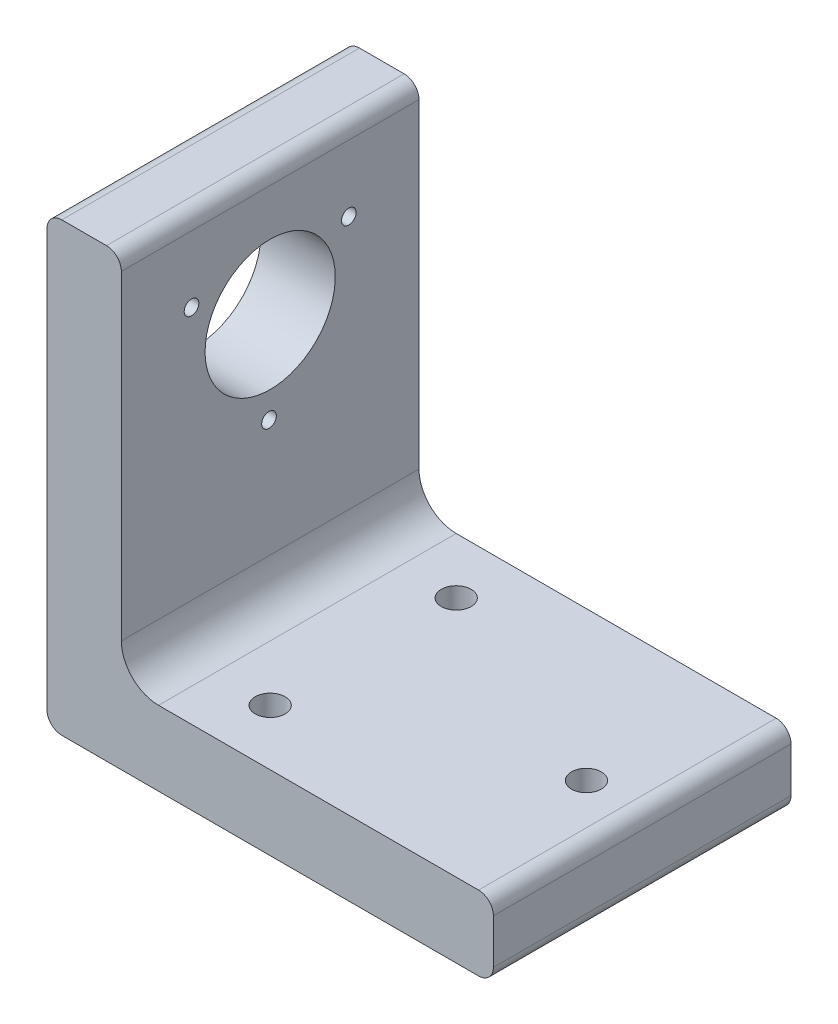
SolidWorks part; units mm, degrees
material "6061 Alloy"
ref_plane "Front" through (0, 0, 0) normal (0, 0, 1) x (1, 0, 0)
ref_plane "Top" through (0, 0, 0) normal (0, 1, 0) x (1, 0, 0)
ref_plane "Right" through (0, 0, 0) normal (1, 0, 0) x (0, 0, -1)
sketch "Sketch1" plane through (0, 0, 0) normal (0, 0, 1) x (1, 0, 0)
  line L0 (0, 0) -> (0, 76.2)
  line L1 (0, -50) -> (0, 50) construction
  line L2 (0, 76.2) -> (12.7, 76.2)
  line L3 (12.7, 76.2) -> (12.7, 12.7)
  line L4 (12.7, 12.7) -> (76.2, 12.7)
  line L5 (76.2, 12.7) -> (76.2, 0)
  line L6 (50, 0) -> (-50, 0) construction
  line L7 (76.2, 0) -> (0, 0)
  dimension "D1" = 76.2
  dimension "D2" = 12.7
extrude "Boss-Extrude1" add sketch "Sketch1" along normal blind 50.8
fillet "Fillet1" radius 2.54 5 edges at (12.7, 76.2, 25.4) (0, 76.2, 25.4) (0, 0, 25.4) (76.2, 0, 25.4) (76.2, 12.7, 25.4)
fillet "Fillet2" radius 6.35 1 edges at (12.7, 12.7, 25.4)
sketch "Sketch2" plane through (12.7, 0, 0) normal (1, 0, 0) x (0, 0, -1)
  line L0 (-50.8, 54.61) -> (0, 54.61) construction
  line L1 (-50.8, 19.05) -> (-50.8, 73.66) construction
  line L2 (0, 19.05) -> (0, 73.66) construction
  line L3 (-50.8, 76.2) -> (0, 76.2) construction
  circle A0 centre (-25.4, 54.61) radius 11.1125
  dimension "D1" = 22.225
  dimension "D2" = 21.59
extrude "Cut-Extrude1" cut sketch "Sketch2" against normal through all
hole_wizard "M3x0.5 Tapped Hole1" positions "Sketch3" profile "Sketch4" tap size "M3x0.5" standard "ANSI Metric" end condition up to next
sketch "Sketch3" plane through (12.7, 0, 0) normal (1, 0, 0) x (0, 0, -1)
  line L0 (-38.8234, 62.36) -> (-25.4, 54.61) construction
  line L1 (-25.4, 54.61) -> (-25.4, 39.11) construction
  line L3 (-25.4, 54.61) -> (-11.9766, 62.36) construction
  circle A0 centre (-25.4, 54.61) radius 15.5 construction
  circle A1 centre (-25.4, 54.61) radius 11.1125 construction
  point P0 (-38.8234, 62.36)
  point P2 (-11.9766, 62.36)
  point P4 (-25.6015, 39.1113)
  dimension "D1" = 31
  dimension "D2" = 120
  dimension "D3" = 120
sketch "Sketch4" plane through (12.7, 62.36, 38.8234) normal (0, 1, 0) x (0, 0, -1)
  line L0 (0, 0) -> (0, 12.7)
  line L1 (0, 12.7) -> (1.25, 12.7)
  line L2 (1.25, 12.7) -> (1.25, 0)
  line L5 (1.25, 0) -> (0, 0)
  line L11 (0, -6.35) -> (0, 107.95) construction
  dimension "Thru Tap Drill Dia." = 2.5
  dimension "Thru Tap Drill Depth" = 12.7
cosmetic thread "Hole Thread1" parameters "D2"=3
cosmetic thread "Hole Thread2" parameters "D2"=3
cosmetic thread "Hole Thread3" parameters "D2"=3
hole_wizard "1/4-20 Tapped Hole1" positions "Sketch5" profile "Sketch6" tap size "1/4-20" standard "ANSI Inch" end condition up to next
sketch "Sketch5" plane through (0, 12.7, 0) normal (0, 1, 0) x (1, 0, 0)
  line L0 (66.675, -25.4) -> (76.2, -25.4) construction
  line L1 (76.2, 0) -> (76.2, -50.8) construction
  line L3 (28.575, 0) -> (28.575, -9.525) construction
  line L4 (73.66, 0) -> (19.05, 0) construction
  line L7 (28.575, -41.275) -> (28.575, -50.8) construction
  line L8 (73.66, -50.8) -> (19.05, -50.8) construction
  line L10 (28.575, -9.525) -> (76.2, -9.525) construction
  line L11 (76.2, -50.8) -> (76.2, 0) construction
  point P0 (28.575, -9.525)
  point P2 (28.575, -41.275)
  point P4 (66.675, -25.4)
  dimension "D1" = 9.525
  dimension "D2" = 47.625
sketch "Sketch6" plane through (28.575, 12.7, 9.525) normal (1, 0, 0) x (0, 0, 1)
  line L0 (0, 0) -> (0, 12.7)
  line L1 (0, 12.7) -> (2.5527, 12.7)
  line L2 (2.5527, 12.7) -> (2.5527, 0)
  line L5 (2.5527, 0) -> (0, 0)
  line L11 (0, -6.35) -> (0, 107.95) construction
  dimension "Thru Tap Drill Dia." = 5.1054
  dimension "Thru Tap Drill Depth" = 12.7
cosmetic thread "Hole Thread4" parameters "D2"=6.35
cosmetic thread "Hole Thread5" parameters "D2"=6.35
cosmetic thread "Hole Thread6" parameters "D2"=6.35
